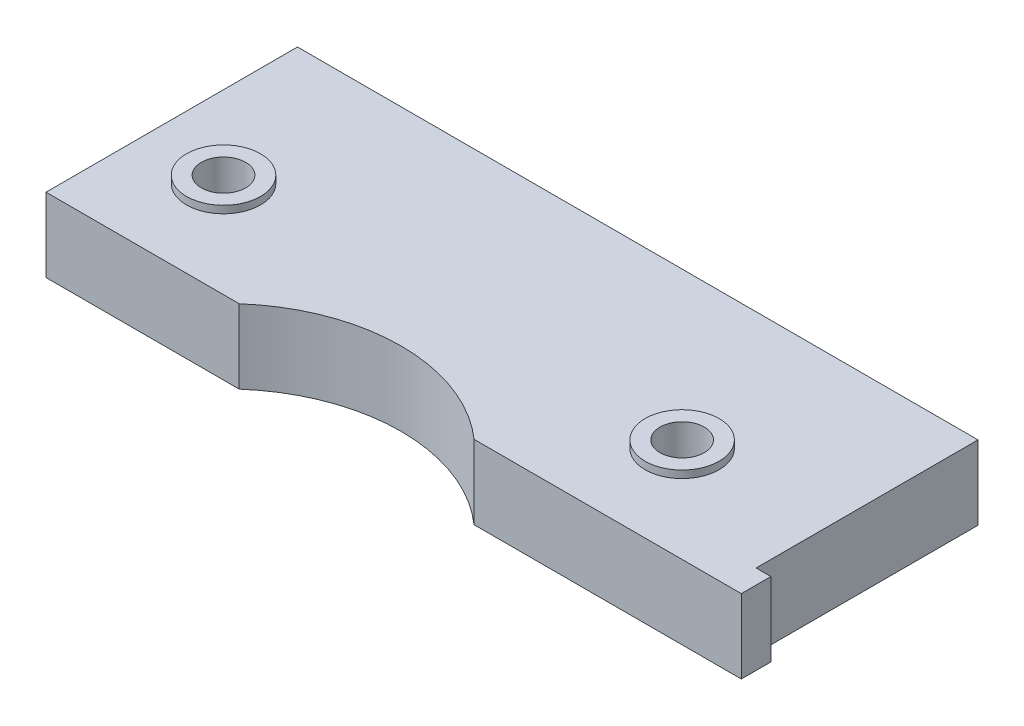
SolidWorks part; units mm, degrees
material "ABS"
ref_plane "Front Plane" through (0, 0, 0) normal (0, 0, 1) x (1, 0, 0)
ref_plane "Top Plane" through (0, 0, 0) normal (0, 1, 0) x (1, 0, 0)
ref_plane "Right Plane" through (0, 0, 0) normal (1, 0, 0) x (0, 0, -1)
sketch "Sketch1" plane through (0, 0, 0) normal (0, 1, 0) x (1, 0, 0)
  line L0 (40.5, -6.5) -> (41.5, -6.5)
  line L1 (-5.5, 10.5) -> (40.5, 10.5)
  line L2 (-5.5, 10.5) -> (-5.5, -6.5)
  line L3 (-5.5, -6.5) -> (7.5627, -6.5)
  line L4 (40.5, 10.5) -> (40.5, -4.5)
  line L5 (41.5, -6.5) -> (41.5, -4.5)
  line L6 (41.5, -4.5) -> (40.5, -4.5)
  line L7 (23.4373, -6.5) -> (40.5, -6.5)
  circle A0 centre (0, 0) radius 1.5
  circle A1 centre (31, 0) radius 1.5
  arc A2 (23.4373, -6.5) -> (7.5627, -6.5) centre (15.5, -15.5) ccw
  dimension "D1" = 3
  dimension "D4" = 5.5
  dimension "D6" = 6.5
  dimension "D11" = 24
  dimension "D2" = 31
  dimension "D3" = 46
  dimension "D5" = 17
  dimension "D7" = 1
  dimension "D8" = 2
  dimension "D9" = 15.5
  dimension "D10" = 15.5
extrude "Boss-Extrude1" add sketch "Sketch1" along normal blind 5
sketch "Sketch2" plane through (0, 5, 0) normal (0, 1, 0) x (1, 0, 0)
  circle A0 centre (0, 0) radius 2.5
  circle A1 centre (31, 0) radius 2.5
  circle A2 centre (31, 0) radius 1.5
  circle A3 centre (0, 0) radius 1.5
  dimension "D1" = 5
extrude "Boss-Extrude2" add sketch "Sketch2" along normal blind 0.5
